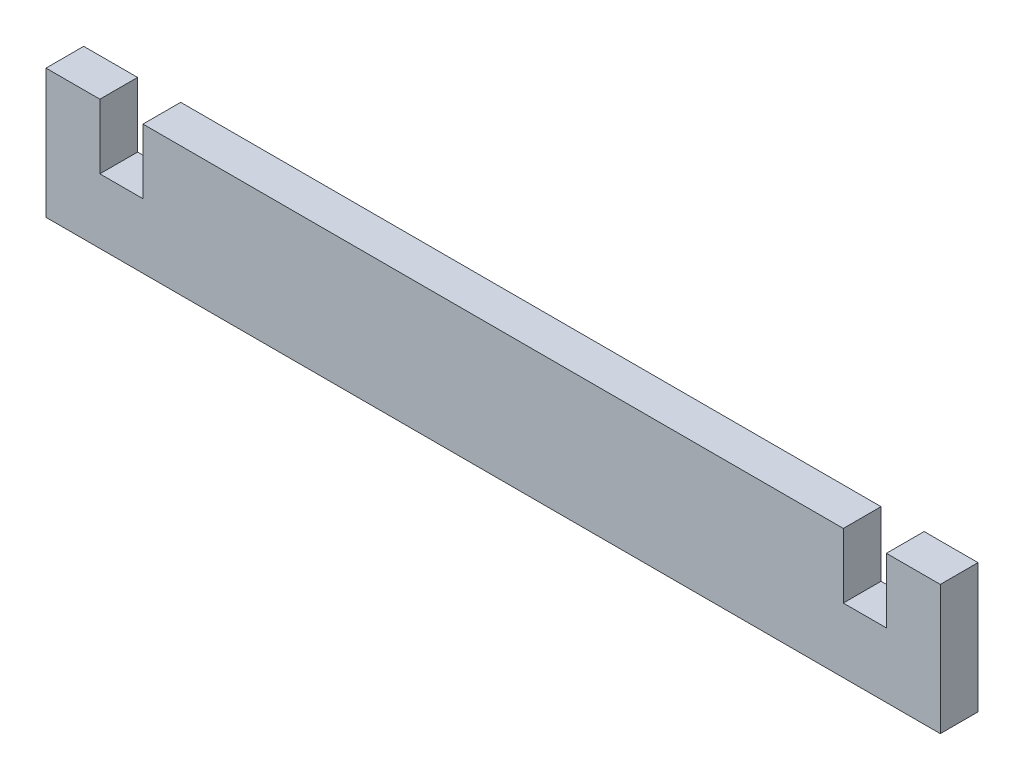
SolidWorks part; units mm, degrees
ref_plane "Front Plane" through (0, 0, 0) normal (0, 0, 1) x (1, 0, 0)
ref_plane "Top Plane" through (0, 0, 0) normal (0, 1, 0) x (1, 0, 0)
ref_plane "Right Plane" through (0, 0, 0) normal (1, 0, 0) x (0, 0, -1)
sketch "Sketch1" plane through (0, 0, 0) normal (0, 0, 1) x (1, 0, 0)
  line L0 (0, 6) -> (0, -6) construction
  line L1 (-32.5, 6) -> (32.5, 6)
  line L2 (32.5, 6) -> (32.5, 0)
  line L3 (32.5, 0) -> (36.5, 0)
  line L4 (36.5, 0) -> (36.5, 6)
  line L5 (36.5, 6) -> (41.5, 6)
  line L6 (41.5, 6) -> (41.5, -6)
  line L7 (41.5, -6) -> (-41.5, -6)
  line L8 (-36.5, 0) -> (-36.5, 6)
  line L9 (-41.5, 6) -> (-41.5, -6)
  line L10 (-36.5, 6) -> (-41.5, 6)
  line L11 (-32.5, 0) -> (-36.5, 0)
  line L12 (-32.5, 6) -> (-32.5, 0)
  point P6 (58.2404, -6)
  dimension "D1" = 12
  dimension "D2" = 4
  dimension "D3" = 5
  dimension "D4" = 32.5
extrude "Boss-Extrude1" add sketch "Sketch1" along normal blind 3.5
equation "\"Lenght\"= 65"
equation "\"D4@Sketch1\"=\"Lenght\"/2"
